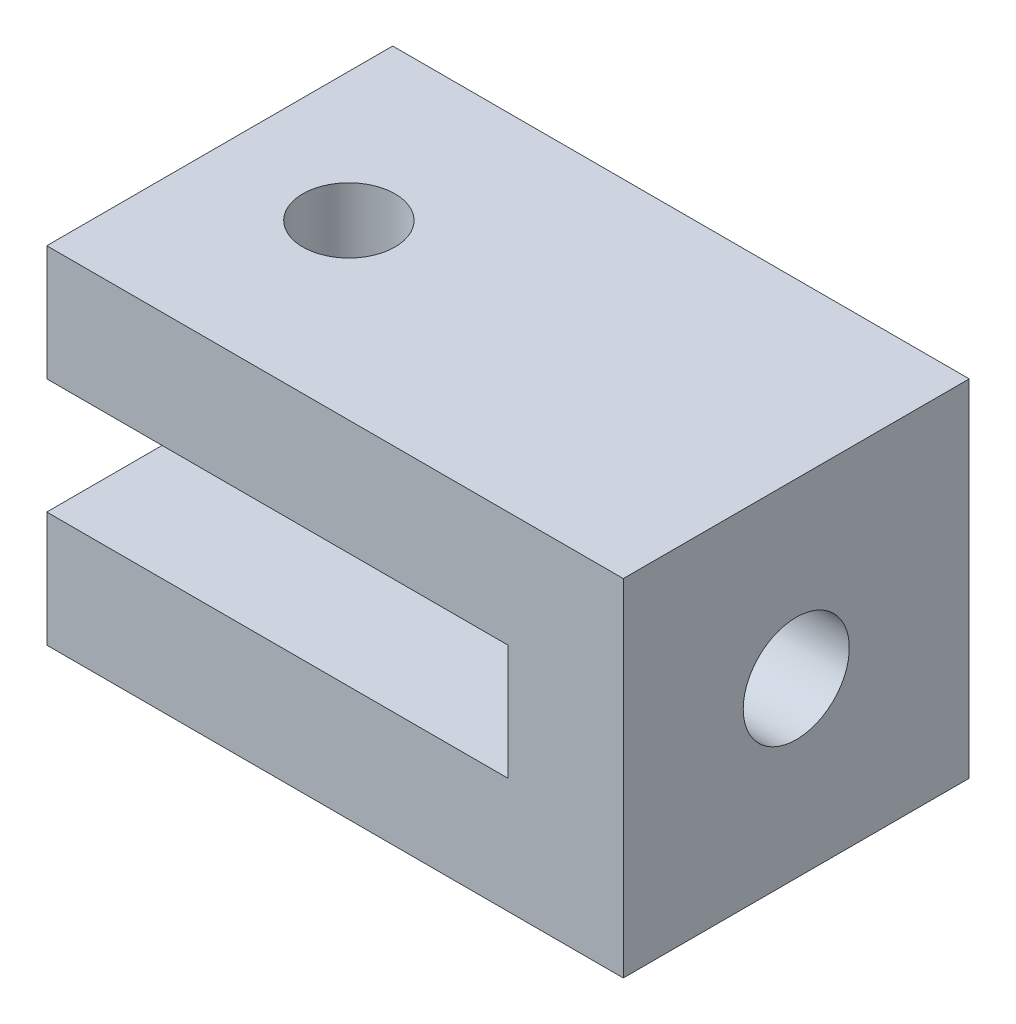
SolidWorks part; units mm, degrees
ref_plane "Front Plane" through (0, 0, 0) normal (0, 0, 1) x (1, 0, 0)
ref_plane "Top Plane" through (0, 0, 0) normal (0, 1, 0) x (1, 0, 0)
ref_plane "Right Plane" through (0, 0, 0) normal (1, 0, 0) x (0, 0, -1)
sketch "Sketch1" plane through (0, 0, 0) normal (0, 1, 0) x (1, 0, 0)
  line L1 (-7.9375, 4.7625) -> (7.9375, 4.7625)
  line L2 (-7.9375, 4.7625) -> (-7.9375, -4.7625)
  line L3 (-7.9375, -4.7625) -> (7.9375, -4.7625)
  line L4 (7.9375, 4.7625) -> (7.9375, -4.7625)
  line L5 (-7.9375, 4.7625) -> (7.9375, -4.7625) construction
  line L6 (-7.9375, -4.7625) -> (7.9375, 4.7625) construction
  point P0 (0, 0)
  dimension "D1" = 9.525
  dimension "D2" = 15.875
extrude "Boss-Extrude1" add sketch "Sketch1" along normal blind 9.525
sketch "Sketch2" plane through (-7.9375, 0, 0) normal (-1, 0, 0) x (0, 0, 1)
  line L0 (4.7625, 9.525) -> (4.7625, 0) construction
  line L1 (-4.7625, 6.35) -> (4.7625, 6.35)
  line L2 (-4.7625, 6.35) -> (-4.7625, 3.175)
  line L3 (-4.7625, 3.175) -> (4.7625, 3.175)
  line L4 (4.7625, 6.35) -> (4.7625, 3.175)
  line L5 (-4.7625, 6.35) -> (4.7625, 3.175) construction
  line L6 (-4.7625, 3.175) -> (4.7625, 6.35) construction
  line L7 (-4.7625, 0) -> (4.7625, 0) construction
  point P0 (0, 4.7625)
  dimension "D1" = 9.525
  dimension "D2" = 3.175
  dimension "D3" = 3.175
extrude "Cut-Extrude1" cut sketch "Sketch2" against normal blind 12.7
sketch "Sketch3" plane through (0, 0, 0) normal (0, -1, 0) x (1, 0, 0)
  line L0 (-7.9375, -4.7625) -> (-7.9375, 4.7625) construction
  line L1 (-7.9375, 4.7625) -> (7.9375, 4.7625) construction
  circle A0 centre (-4.3815, 0) radius 1.27
  dimension "D1" = 3.556
  dimension "D2" = 2.54
  dimension "D3" = 4.7625
extrude "Cut-Extrude2" cut sketch "Sketch3" against normal blind 9.525
sketch "Sketch4" plane through (4.7625, 0, 0) normal (-1, 0, 0) x (0, 0, 1)
  circle A0 centre (0, 4.7625) radius 1.4605
  dimension "D1" = 2.921
extrude "Cut-Extrude3" cut sketch "Sketch4" against normal blind 3.175
